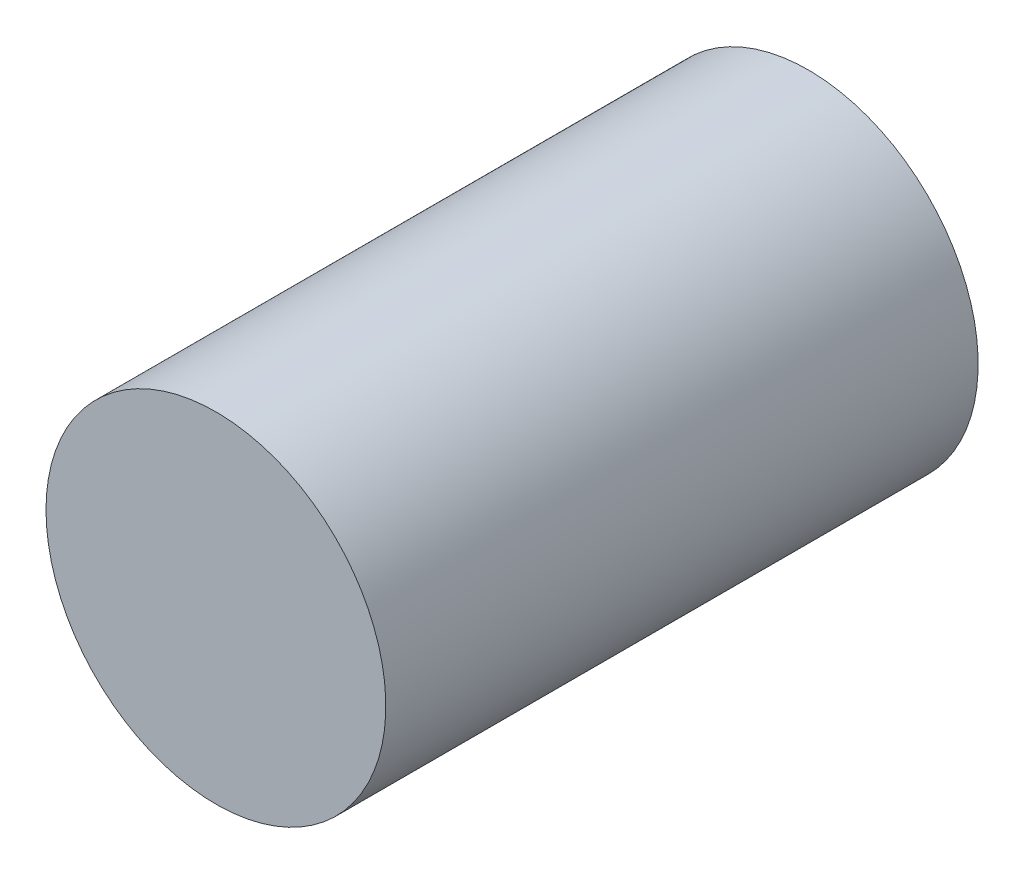
SolidWorks part; units mm, degrees
material "motor"
ref_plane "Front Plane" through (0, 0, 0) normal (0, 0, 1) x (1, 0, 0)
ref_plane "Top Plane" through (0, 0, 0) normal (0, 1, 0) x (1, 0, 0)
ref_plane "Right Plane" through (0, 0, 0) normal (1, 0, 0) x (0, 0, -1)
sketch "Sketch1" plane through (0, 0, 0) normal (0, 0, 1) x (1, 0, 0)
  circle A0 centre (0, 0) radius 17.5006
extrude "Boss-Extrude1" add sketch "Sketch1" along normal blind 61.0108
